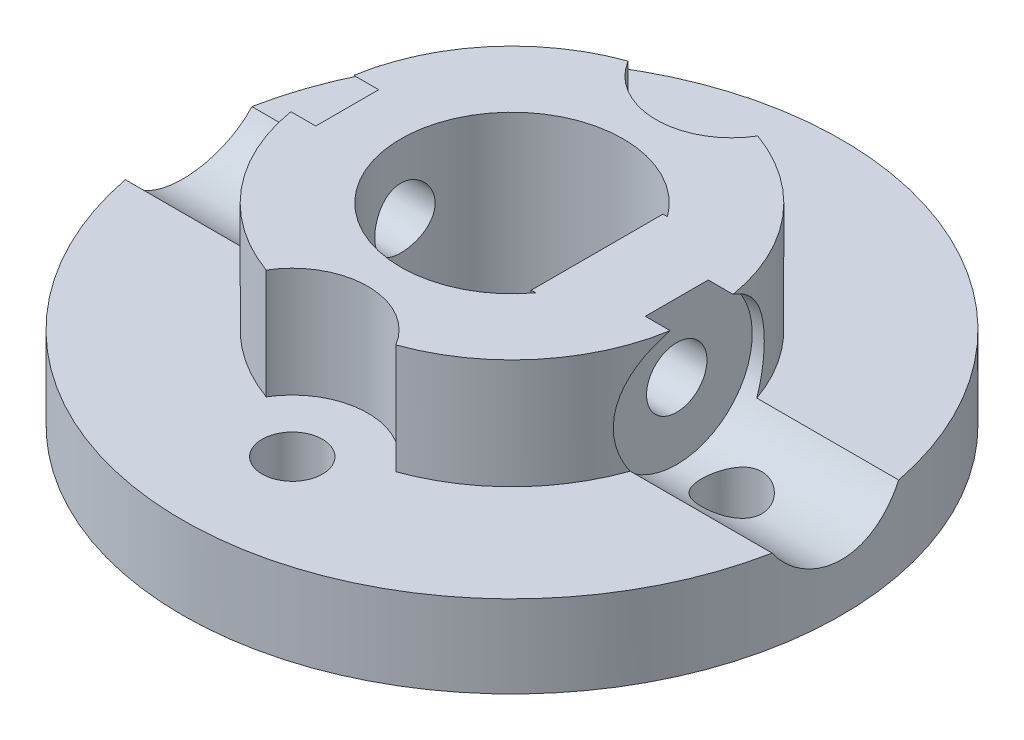
SolidWorks part; units mm, degrees
ref_plane "Front Plane" through (0, 0, 0) normal (0, 0, 1) x (1, 0, 0)
ref_plane "Top Plane" through (0, 0, 0) normal (0, 1, 0) x (1, 0, 0)
ref_plane "Right Plane" through (0, 0, 0) normal (1, 0, 0) x (0, 0, -1)
sketch "Stock_horn_drive_flange_profile" plane through (0, 0, 0) normal (0, 1, 0) x (1, 0, 0)
  circle A0 centre (0, 0) radius 12
  circle A1 centre (0, 0) radius 4.05
  dimension "D1" = 24
  dimension "D2" = 8.1
extrude "Stock_horn_drive_flange" add sketch "Stock_horn_drive_flange_profile" along normal blind 3 from offset 41
sketch "D_coupling_ring_profile" plane through (0, 0, 0) normal (0, 1, 0) x (1, 0, 0)
  circle A0 centre (0, 0) radius 7
  circle A1 centre (0, 0) radius 4.05
  dimension "D1" = 14
  dimension "D2" = 8.1
extrude "D_coupling_ring" add sketch "D_coupling_ring_profile" along normal blind 4 from offset 44
sketch "D_key_land_profile" plane through (0, 0, 0) normal (0, 1, 0) x (1, 0, 0)
  line L1 (3.1, -2.4) -> (6, -2.4)
  line L2 (3.1, -2.4) -> (3.1, 2.4)
  line L3 (3.1, 2.4) -> (6, 2.4)
  line L4 (6, -2.4) -> (6, 2.4)
  dimension "D1" = 2.9
  dimension "D2" = 4.8
  dimension "D3" = 3.1
  dimension "D4" = 2.4
extrude "D_key_land" add sketch "D_key_land_profile" along normal blind 4 from offset 44
sketch "Stock_horn_screws_profile" plane through (0, 0, 0) normal (0, 1, 0) x (1, 0, 0)
  circle A0 centre (-8, 0) radius 1.1
  circle A1 centre (8, 0) radius 1.1
  circle A2 centre (0, -8) radius 1.1
  circle A3 centre (0, 8) radius 1.1
  dimension "D1" = 2.2
  dimension "D2" = 2.2
  dimension "D3" = 2.2
  dimension "D4" = 2.2
  dimension "D5" = 8
  dimension "D6" = 8
  dimension "D7" = 8
  dimension "D8" = 8
extrude "Stock_horn_screws" cut sketch "Stock_horn_screws_profile" along normal through all from offset 39
sketch "Two_horn_washer_clearances_profile" plane through (0, 0, 0) normal (0, 1, 0) x (1, 0, 0)
  circle A0 centre (0, -8) radius 2.75
  circle A1 centre (0, 8) radius 2.75
  dimension "D1" = 5.5
  dimension "D2" = 5.5
  dimension "D3" = 8
  dimension "D4" = 8
extrude "Two_horn_washer_clearances" cut sketch "Two_horn_washer_clearances_profile" along normal blind 4 from offset 44
sketch "Yaw_positive_retention_crossbolt_profile" plane through (0, 0, 0) normal (1, 0, 0) x (0, 0, -1)
  circle A0 centre (0, 45.5) radius 1.1
  dimension "D1" = 2.2
  dimension "D2" = 45.5
extrude "Yaw_positive_retention_crossbolt" cut sketch "Yaw_positive_retention_crossbolt_profile" along normal through all from offset 10
sketch "Crossbolt_flat_seat_-12" plane through (0, 0, 0) normal (1, 0, 0) x (0, 0, -1)
  circle A0 centre (0, 45.5) radius 2.75
  dimension "D1" = 5.5
  dimension "D2" = 45.5
extrude "Crossbolt_flat_seat_cut_-12" cut sketch "Crossbolt_flat_seat_-12" along normal blind 6 from offset 12
sketch "Crossbolt_flat_seat_6" plane through (0, 0, 0) normal (1, 0, 0) x (0, 0, -1)
  circle A0 centre (0, 45.5) radius 2.75
  dimension "D1" = 5.5
  dimension "D2" = 45.5
extrude "Crossbolt_flat_seat_cut_6" cut sketch "Crossbolt_flat_seat_6" along normal blind 6 from offset 6
